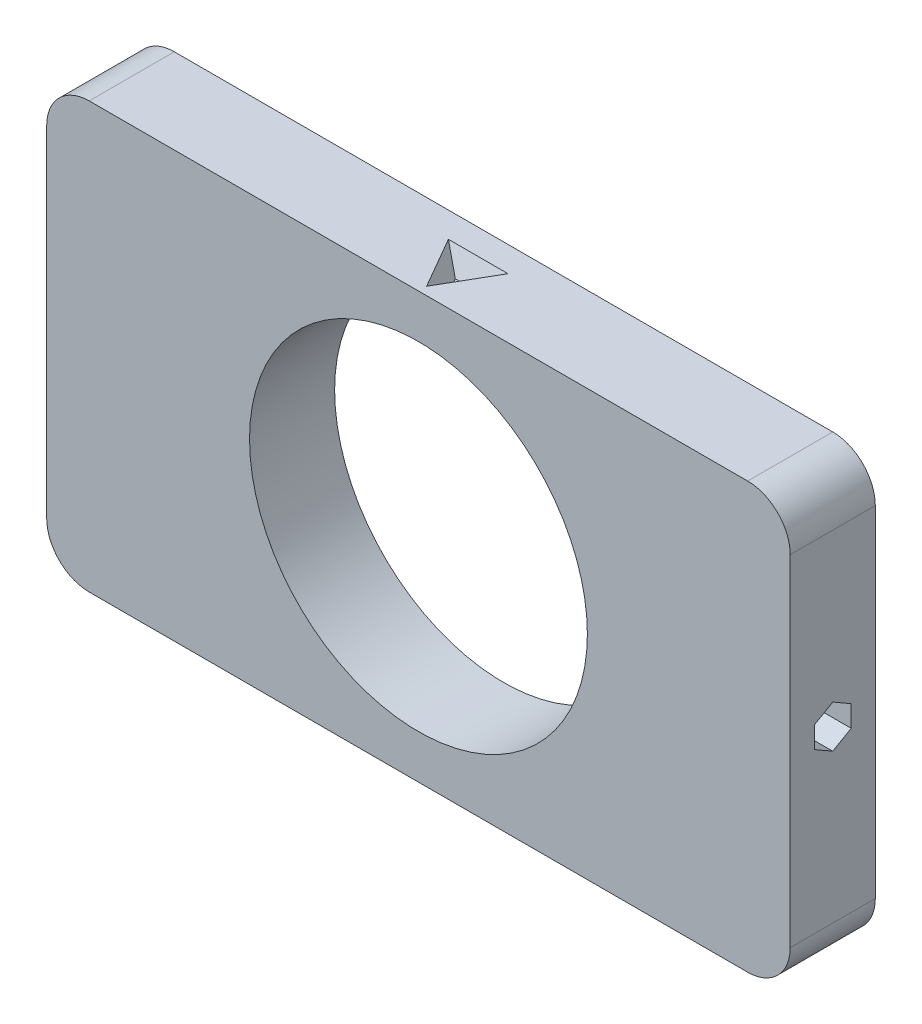
SolidWorks part; units mm, degrees
ref_plane "Front Plane" through (0, 0, 0) normal (0, 0, 1) x (1, 0, 0)
ref_plane "Top Plane" through (0, 0, 0) normal (0, 1, 0) x (1, 0, 0)
ref_plane "Right Plane" through (0, 0, 0) normal (1, 0, 0) x (0, 0, -1)
sketch "Sketch1" plane through (0, 0, 0) normal (0, 0, 1) x (1, 0, 0)
  line L1 (77.3807, -49.9899) -> (-77.3807, -49.9899)
  line L2 (87.3807, -39.9899) -> (87.3807, 39.9899)
  line L3 (77.3807, 49.9899) -> (-77.3807, 49.9899)
  line L4 (-87.3807, -39.9899) -> (-87.3807, 39.9899)
  line L5 (87.3807, -49.9899) -> (-87.3807, 49.9899) construction
  line L6 (87.3807, 49.9899) -> (-87.3807, -49.9899) construction
  circle A0 centre (0, 0) radius 39.7052
  arc A1 (-77.3807, -49.9899) -> (-87.3807, -39.9899) centre (-77.3807, -39.9899) cw
  arc A2 (77.3807, -49.9899) -> (87.3807, -39.9899) centre (77.3807, -39.9899) ccw
  arc A3 (87.3807, 39.9899) -> (77.3807, 49.9899) centre (77.3807, 39.9899) ccw
  arc A4 (-77.3807, 49.9899) -> (-87.3807, 39.9899) centre (-77.3807, 39.9899) ccw
  point P0 (0, 0)
  dimension "D1" = 10
extrude "Boss-Extrude1" add sketch "Sketch1" along normal blind 20
sketch "Sketch2" plane through (0, 49.9899, 0) normal (0, 1, 0) x (1, 0, 0)
  line L0 (0, 0) -> (0, -20) construction
  line L1 (0, -18.0829) -> (7, -5.9585)
  line L2 (7, -5.9585) -> (-7, -5.9585)
  line L3 (-7, -5.9585) -> (0, -18.0829)
  line L4 (77.3807, 0) -> (-77.3807, 0) construction
  line L5 (77.3807, -20) -> (-77.3807, -20) construction
  circle A0 centre (0, -10) radius 4.0415 construction
  point P1 (0, 0)
  dimension "D1" = 14
extrude "Cut-Extrude1" cut sketch "Sketch2" against normal blind 5 draft 24
sketch "Sketch3" plane through (87.3807, 0, 0) normal (1, 0, 0) x (0, 0, -1)
  line L0 (-20, 0) -> (0, 0) construction
  line L1 (-10, 5) -> (-14.3301, 2.5)
  line L2 (-14.3301, 2.5) -> (-14.3301, -2.5)
  line L3 (-14.3301, -2.5) -> (-10, -5)
  line L4 (-10, -5) -> (-5.6699, -2.5)
  line L5 (-5.6699, -2.5) -> (-5.6699, 2.5)
  line L6 (-5.6699, 2.5) -> (-10, 5)
  line L7 (-20, -39.9899) -> (-20, 39.9899) construction
  circle A0 centre (-10, 0) radius 4.3301 construction
  point P1 (0, 0)
  dimension "D1" = 5
extrude "Cut-Extrude2" cut sketch "Sketch3" against normal up to next
